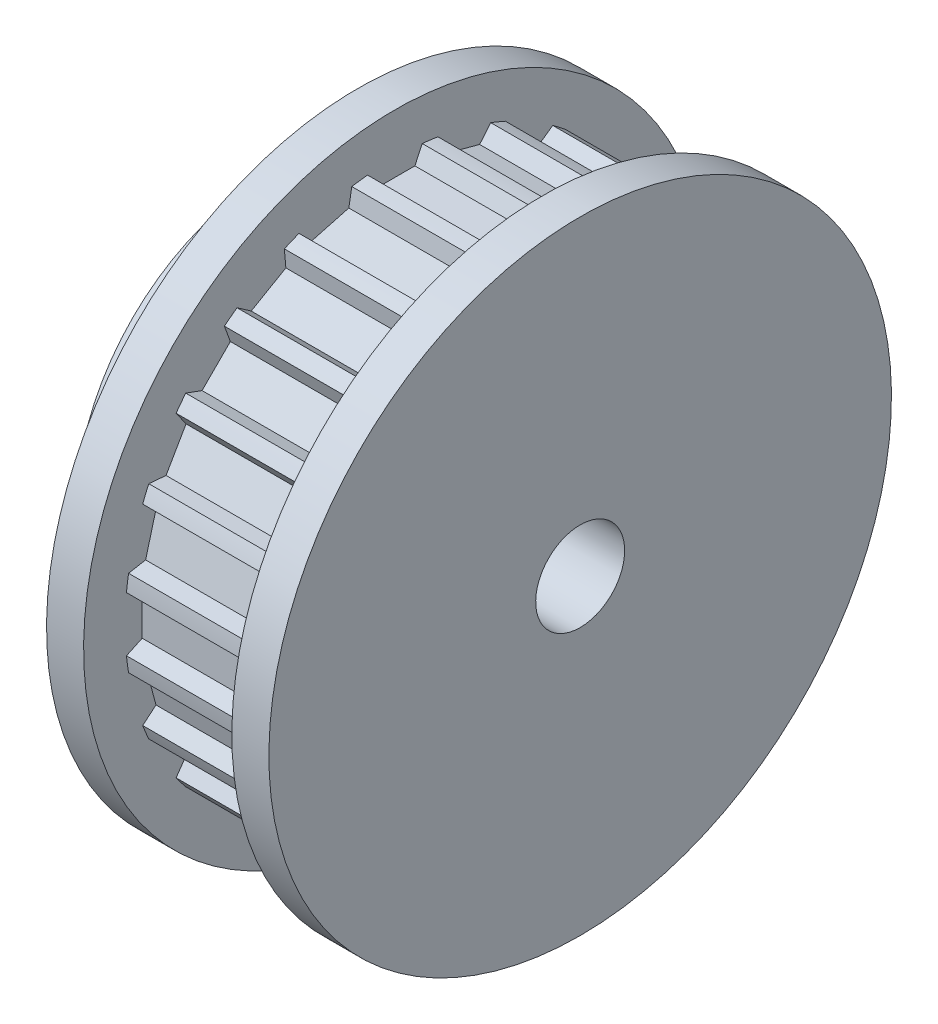
SolidWorks part; units mm, degrees
ref_plane "Front Plane" through (0, 0, 0) normal (0, 0, 1) x (1, 0, 0)
ref_plane "Top Plane" through (0, 0, 0) normal (0, 1, 0) x (1, 0, 0)
ref_plane "Right Plane" through (0, 0, 0) normal (1, 0, 0) x (0, 0, -1)
sketch "Sketch2" plane through (0, 0, 0) normal (1, 0, 0) x (0, 0, -1)
  line L3 (0, 0) -> (0, 17.1) construction
  line L6 (0, -17.2) -> (0, -19.2) construction
  line L7 (-1.3951, 17.1433) -> (-1.35, 17.0466)
  line L8 (1.3951, 17.1433) -> (1.35, 17.0466)
  line L9 (-1.3951, 17.1433) -> (-1.8441, 18.1063)
  line L10 (1.3951, 17.1433) -> (1.8441, 18.1063)
  line L12 (-1.35, 17.0466) -> (1.35, 17.0466)
  line L14 (0, 17.2) -> (0, 19.2) construction
  line L15 (0, 0) -> (0, -4.5) construction
  circle A0 centre (0, 0) radius 19.2 construction
  circle A1 centre (0, 0) radius 17.1 construction
  circle A2 centre (0, 0) radius 17.2 construction
  arc A7 (1.8441, 18.1063) -> (-1.8441, 18.1063) centre (0, 0) ccw
  point P5 (0, 18.2)
  dimension "D1" = 50
  dimension "PD" = 38.4
  dimension "D2" = 2
  dimension "D4" = 2.7
  dimension "D3" = 1.1
  dimension "D5" = 3.6883
  dimension "hs" = 4.5
sketch "Sketch1" plane through (0, 0, 0) normal (0, 0, 1) x (1, 0, 0)
  line L0 (-10.5, 0) -> (10.5, 0) construction
  line L1 (-10.5, 3) -> (10.5, 3)
  line L2 (-10.5, 3) -> (-10.5, 13)
  line L3 (-4.5, 21) -> (-2, 21)
  line L4 (-2, 18.2) -> (-2, 18.45)
  line L5 (-2, 34.8083) -> (-2, 18.2) construction
  line L6 (-2, 18.2) -> (8, 18.2)
  line L7 (8, 18.2) -> (8, 18.45)
  line L8 (-2, 21) -> (-2, 18.45)
  line L9 (8, 21) -> (10.5, 21)
  line L10 (10.5, 21) -> (10.5, 3)
  line L11 (8, 21) -> (8, 18.45)
  line L12 (-7.5, 13) -> (-7.5, 3) construction
  line L13 (-4.5, 21) -> (-4.5, 13)
  line L14 (-4.5, 13) -> (-10.5, 13)
  dimension "Bore Size" = 6
  dimension "Overall Width" = 21
  dimension "Inside Width" = 10
  dimension "Outside Width" = 15
  dimension "Hub Dia" = 26
  dimension "OD" = 42
  dimension "D4" = 0.25
revolve "Revolve1" add sketch "Sketch1" angle 360 mid plane about L0
sketch "Sketch3" plane through (-2, 0, 0) normal (1, 0, 0) x (0, 0, -1)
  line L2 (-1.3951, 17.1433) -> (-1.35, 17.0466) construction
  line L3 (-1.35, 17.0466) -> (1.35, 17.0466) construction
  line L4 (1.3951, 17.1433) -> (1.35, 17.0466) construction
  line L5 (-1.8441, 18.1063) -> (-1.35, 17.0466)
  line L6 (-1.35, 17.0466) -> (1.35, 17.0466)
  line L7 (1.8441, 18.1063) -> (1.35, 17.0466)
  arc A1 (1.8441, 18.1063) -> (-1.8441, 18.1063) centre (0, 0) ccw construction
  arc A2 (1.8441, 18.1063) -> (-1.8441, 18.1063) centre (0, 0) ccw
extrude "Cut-Extrude1" cut sketch "Sketch3" along normal up to surface (10 mm away) up to face at (8, -18.2, 0)
pattern_circular "CirPattern1" count 24 over 360 about axis through (0, 0, 0) along (1, 0, 0) of "Cut-Extrude1"
